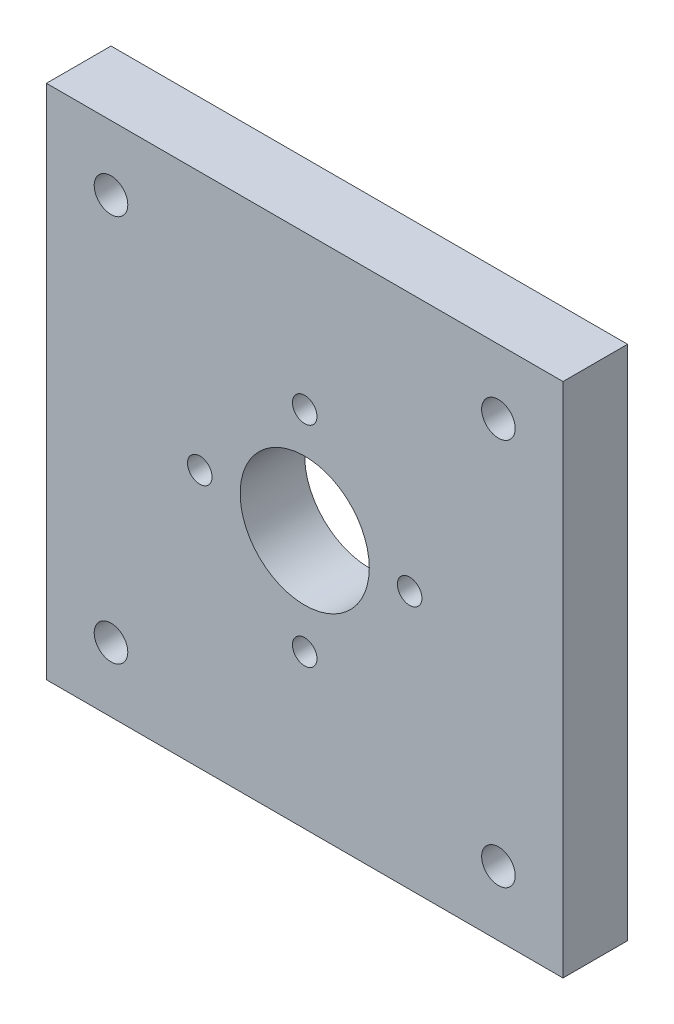
SolidWorks part; units mm, degrees
ref_plane "Front Plane" through (0, 0, 0) normal (0, 0, 1) x (1, 0, 0)
ref_plane "Top Plane" through (0, 0, 0) normal (0, 1, 0) x (1, 0, 0)
ref_plane "Right Plane" through (0, 0, 0) normal (1, 0, 0) x (0, 0, -1)
sketch "Sketch1" plane through (0, 0, 0) normal (0, 0, 1) x (1, 0, 0)
  line L0 (0, 0) -> (0, 1814.6408) construction
  line L1 (2, 1.7586) -> (-2, 1.7586)
  line L2 (-2, 1.7586) -> (-2, -2.2414)
  line L3 (-2, -2.2414) -> (2, -2.2414)
  line L4 (2, 1.7586) -> (2, -2.2414)
  line L5 (2, -0.2414) -> (-49998, -0.2414) construction
  circle A0 centre (-1.5, 1.2586) radius 0.13
  circle A1 centre (-1.5, -1.7414) radius 0.13
  circle A2 centre (1.5, -1.7414) radius 0.13
  circle A3 centre (1.5, 1.2586) radius 0.13
  circle A4 centre (0, -0.2414) radius 0.8125 construction
  circle A5 centre (0, -0.2414) radius 0.5
  circle A6 centre (0, 0.5711) radius 0.095
  circle A7 centre (0.8125, -0.2414) radius 0.095
  circle A8 centre (0, -1.0539) radius 0.095
  circle A9 centre (-0.8125, -0.2414) radius 0.095
  point P12 (0, -2.2414)
  point P17 (0, 1.7586)
  point P19 (2, -0.2414)
  point P20 (-2, -0.2414)
  dimension "D6" = 0.26
  dimension "D7" = 0.26
  dimension "D12" = 1.625
  dimension "D13" = 1
  dimension "D14" = 0.19
  dimension "D15" = 0.19
  dimension "D16" = 0.19
  dimension "D17" = 0.19
  dimension "D1" = 2
  dimension "D2" = 4
  dimension "D3" = 2
  dimension "D4" = 0.5
  dimension "D5" = 0.5
  dimension "D8" = 0.5
  dimension "D9" = 0.5
  dimension "D10" = 3
  dimension "D11" = 2
extrude "Boss-Extrude2" add sketch "Sketch1" along normal mid plane 0.5
